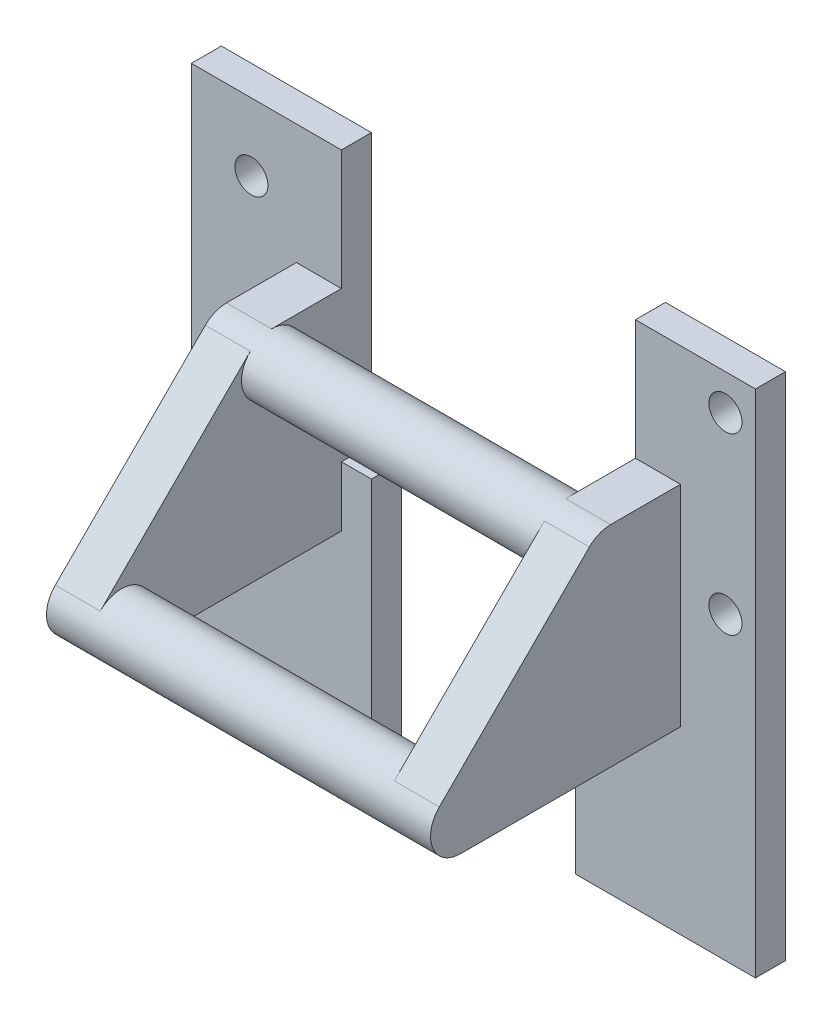
SolidWorks part; units mm, degrees
ref_plane "Front Plane" through (0, 0, 0) normal (0, 0, 1) x (1, 0, 0)
ref_plane "Top Plane" through (0, 0, 0) normal (0, 1, 0) x (1, 0, 0)
ref_plane "Right Plane" through (0, 0, 0) normal (1, 0, 0) x (0, 0, -1)
sketch "Sketch2" plane through (0, 0, 0) normal (0, 0, 1) x (1, 0, 0)
  line L6 (-10, -75) -> (-10, -115)
  line L7 (-10, -115) -> (20, -115)
  line L8 (20, -115) -> (20, -30)
  line L9 (20, -30) -> (5, -30)
  line L10 (5, -30) -> (5, -75)
  line L11 (5, -75) -> (-10, -75)
  line L12 (-10, -75) -> (-10, -115)
  line L13 (-10, -115) -> (20, -115)
  line L14 (20, -115) -> (20, -30)
  line L15 (20, -30) -> (5, -30)
  line L16 (5, -30) -> (5, -75)
  line L17 (5, -75) -> (-10, -75)
  line L18 (-74, -30) -> (-74, -115)
  line L19 (-74, -115) -> (-44, -115)
  line L20 (-44, -115) -> (-44, -75)
  line L21 (-44, -75) -> (-54, -75)
  line L22 (-54, -75) -> (-54, -30)
  line L23 (-54, -30) -> (-74, -30)
  line L24 (-74, -30) -> (-74, -115)
  line L25 (-74, -115) -> (-44, -115)
  line L26 (-44, -115) -> (-44, -75)
  line L27 (-44, -75) -> (-54, -75)
  line L28 (-54, -75) -> (-54, -30)
  line L29 (-54, -30) -> (-74, -30)
  circle A0 centre (-64, -65) radius 2.75 construction
  circle A1 centre (15, -35.9197) radius 2.75 construction
  circle A2 centre (15, -65) radius 2.75 construction
  circle A3 centre (-64, -41.25) radius 2.75 construction
  circle A4 centre (15, -35.9197) radius 2.75
  circle A5 centre (15, -65) radius 2.75
  circle A6 centre (-64, -65) radius 2.75
  circle A7 centre (-64, -41.25) radius 2.75
  dimension "D1" = 0
  dimension "D2" = 0
extrude "Boss-Extrude1" add sketch "Sketch2" along normal blind 5
sketch "Sketch3" plane through (-54, 0, 0) normal (1, 0, 0) x (0, 0, -1)
  line L0 (8.3553, -22.9289) -> (-72.8579, -104.1421) construction
  line L1 (8.3553, -22.9289) -> (-5, -36.2843)
  line L2 (-5, -30) -> (-5, -50)
  line L3 (-5, -115) -> (-5, -30) construction
  line L4 (-5, -50) -> (-18.7157, -50)
  line L5 (-5, -115) -> (-5, -85)
  line L6 (-5, -85) -> (-53.7157, -85)
  line L7 (-18.7157, -50) -> (-53.7157, -85)
  line L8 (-5, -85) -> (-5, -50)
  line M5 (-5, -30) -> (-5, -75)
  dimension "D1" = 20
  dimension "D2" = 30
extrude "Boss-Extrude3" add sketch "Sketch3" against normal blind 2.5 contours L6 L8 L4 L7 M5
sketch "Sketch4" plane through (5, 0, 0) normal (-1, 0, 0) x (0, 0, 1)
  line L8 (0, -30) -> (0, -75)
  line L9 (5, -30) -> (0, -30)
  line L10 (5, -50) -> (5, -30)
  line L11 (18.7157, -50) -> (5, -50)
  line L12 (53.7157, -85) -> (18.7157, -50)
  line L13 (5, -85) -> (53.7157, -85)
  line L14 (5, -75) -> (5, -85)
  line L15 (0, -75) -> (5, -75)
  line L16 (0, -30) -> (0, -75)
  line L17 (5, -30) -> (0, -30)
  line L18 (5, -50) -> (5, -30)
  line L19 (18.7157, -50) -> (5, -50)
  line L20 (53.7157, -85) -> (18.7157, -50)
  line L21 (5, -85) -> (53.7157, -85)
  line L22 (5, -75) -> (5, -85)
  line L23 (0, -75) -> (5, -75)
  dimension "D1" = 0
extrude "Boss-Extrude4" add sketch "Sketch4" against normal blind 2.5
sketch "Sketch5" plane through (-54, 0, 0) normal (1, 0, 0) x (0, 0, -1)
  line L8 (0, -75) -> (0, -30)
  line L9 (0, -30) -> (-5, -30)
  line L10 (-5, -30) -> (-5, -50)
  line L11 (-5, -50) -> (-18.7157, -50)
  line L12 (-18.7157, -50) -> (-53.7157, -85)
  line L13 (-53.7157, -85) -> (-5, -85)
  line L14 (-5, -85) -> (-5, -75)
  line L15 (-5, -75) -> (0, -75)
  line L16 (0, -75) -> (0, -30)
  line L17 (0, -30) -> (-5, -30)
  line L18 (-5, -30) -> (-5, -50)
  line L19 (-5, -50) -> (-18.7157, -50)
  line L20 (-18.7157, -50) -> (-53.7157, -85)
  line L21 (-53.7157, -85) -> (-5, -85)
  line L22 (-5, -85) -> (-5, -75)
  line L23 (-5, -75) -> (0, -75)
  dimension "D1" = 0
extrude "Boss-Extrude5" add sketch "Sketch5" along normal blind 5
sketch "Sketch6" plane through (5, 0, 0) normal (-1, 0, 0) x (0, 0, 1)
  line L8 (0, -30) -> (0, -75)
  line L9 (0, -75) -> (5, -75)
  line L10 (5, -75) -> (5, -85)
  line L11 (5, -85) -> (53.7157, -85)
  line L12 (53.7157, -85) -> (18.7157, -50)
  line L13 (18.7157, -50) -> (5, -50)
  line L14 (5, -50) -> (5, -30)
  line L15 (5, -30) -> (0, -30)
  line L16 (0, -30) -> (0, -75)
  line L17 (0, -75) -> (5, -75)
  line L18 (5, -75) -> (5, -85)
  line L19 (5, -85) -> (53.7157, -85)
  line L20 (53.7157, -85) -> (18.7157, -50)
  line L21 (18.7157, -50) -> (5, -50)
  line L22 (5, -50) -> (5, -30)
  line L23 (5, -30) -> (0, -30)
  dimension "D1" = 0
extrude "Boss-Extrude6" add sketch "Sketch6" along normal blind 5
fillet "Fillet1" radius 5 1 edges at (3.75, -85, 53.7157)
fillet "Fillet2" radius 5 1 edges at (-52.75, -85, 53.7157)
fillet "Fillet3" radius 5 1 edges at (-52.75, -50, 18.7157)
fillet "Fillet4" radius 5 1 edges at (3.75, -50, 18.7157)
sketch "Sketch7" plane through (-49, 0, 0) normal (1, 0, 0) x (0, 0, -1)
  circle A0 centre (-41.6447, -80) radius 5
extrude "Boss-Extrude7" add sketch "Sketch7" along normal up to surface (49 mm away) up to face at (0, -60.8758, 14.6647)
sketch "Sketch8" plane through (-49, 0, 0) normal (1, 0, 0) x (0, 0, -1)
  circle A0 centre (-16.6447, -55) radius 5
extrude "Boss-Extrude8" add sketch "Sketch8" along normal up to surface (49 mm away) up to face at (0, -60.4932, 13.7408)
